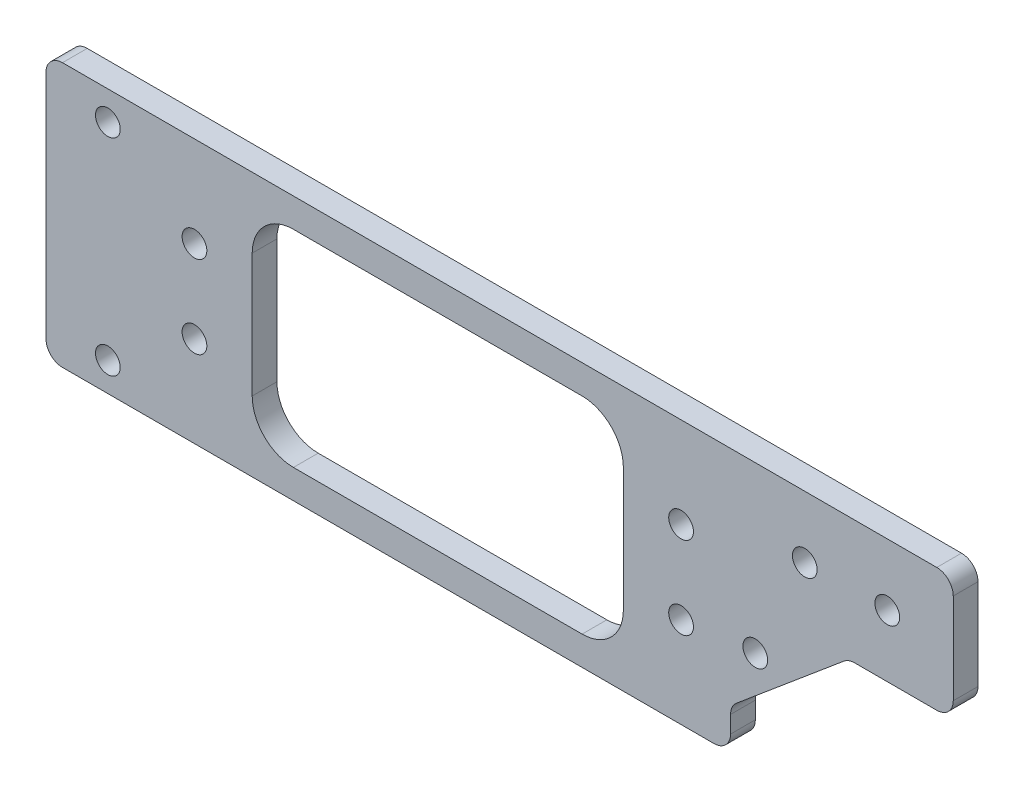
SolidWorks part; units mm, degrees
material "Thornel Mat VMA"
ref_plane "前视基准面" through (0, 0, 0) normal (0, 0, 1) x (1, 0, 0)
ref_plane "上视基准面" through (0, 0, 0) normal (0, 1, 0) x (1, 0, 0)
ref_plane "右视基准面" through (0, 0, 0) normal (1, 0, 0) x (0, 0, -1)
sketch "草图1" plane through (0, 0, 0) normal (0, 0, 1) x (1, 0, 0)
  line L0 (0, 16) -> (0, -16) construction
  line L1 (-47.5, 0) -> (48.6093, 0) construction
  line L2 (-47.5, 16) -> (-47.5, -16)
  line L3 (-47.5, 16) -> (35.5, 16)
  line L5 (35.5, -16) -> (-47.5, -16)
  line L6 (35.5, 16) -> (62.5, 16)
  line L7 (62.5, 16) -> (62.5, 1)
  line L8 (62.5, 1) -> (49.801, 1)
  line L9 (44.5, 8.5) -> (54.5, 8.5) construction
  line L10 (-22.5, -12.5) -> (22.5, -12.5)
  line L11 (-22.5, -12.5) -> (-22.5, 12.5)
  line L12 (-22.5, 12.5) -> (22.5, 12.5)
  line L13 (22.5, -12.5) -> (22.5, 12.5)
  line L14 (-22.5, -12.5) -> (22.5, 12.5) construction
  line L15 (-22.5, 12.5) -> (22.5, -12.5) construction
  line L16 (-40, 16) -> (-40, -16) construction
  line L17 (35.5, -11) -> (49.801, 1)
  line L18 (35.5, -11) -> (35.5, -16)
  circle A0 centre (-29.5, 5) radius 1.5
  circle A1 centre (-29.5, -5) radius 1.5
  circle A2 centre (29.5, 5) radius 1.5
  circle A3 centre (29.5, -5) radius 1.5
  circle A4 centre (44.5, 8.5) radius 1.5
  circle A5 centre (54.5, 8.5) radius 1.5
  circle A6 centre (-40, 12.5) radius 1.5
  circle A7 centre (-40, -12.5) radius 1.5
  circle A8 centre (38.5, -4) radius 1.5
  point P7 (0, 0)
  point P29 (49.5, 8.5)
  dimension "D9" = 3
  dimension "D13" = 3
  dimension "D20" = 3
  dimension "D22" = 3
  dimension "D23" = 25
  dimension "D6" = 7
  dimension "D26" = 5
  dimension "D27" = 3
  dimension "D28" = 3
  dimension "D1" = 32
  dimension "D2" = 16
  dimension "D3" = 83
  dimension "D4" = 15
  dimension "D5" = 47.5
  dimension "D7" = 45
  dimension "D8" = 25
  dimension "D10" = 5
  dimension "D11" = 5
  dimension "D12" = 18
  dimension "D14" = 13
  dimension "D15" = 5
  dimension "D16" = 5
  dimension "D17" = 7.5
  dimension "D18" = 62.5
  dimension "D19" = 8
  dimension "D21" = 7.5
  dimension "D24" = 130
  dimension "D25" = 5
extrude "凸台-拉伸1" add sketch "草图1" along normal blind 3
fillet "圆角1" radius 2 7 edges at (62.5, 1, 1.5) (62.5, 16, 1.5) (-47.5, -16, 1.5) (-47.5, 16, 1.5) (35.5, -16, 1.5) (35.5, -11, 1.5) (49.801, 1, 1.5)
fillet "圆角2" radius 5 4 edges at (-22.5, -12.5, 1.5) (22.5, -12.5, 1.5) (22.5, 12.5, 1.5) (-22.5, 12.5, 1.5)
